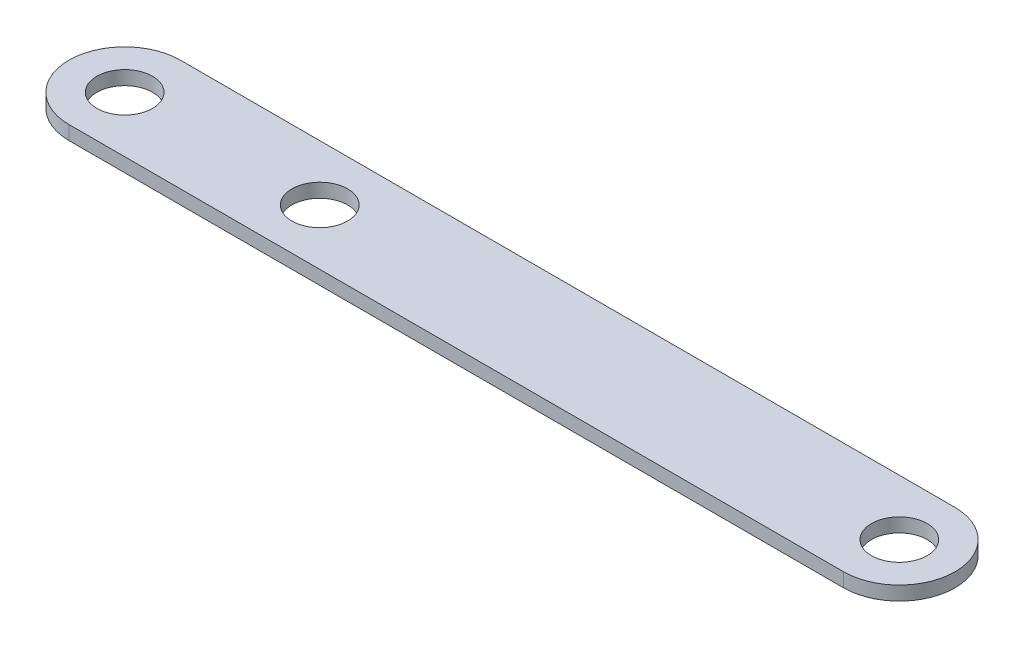
SolidWorks part; units mm, degrees
ref_plane "Front Plane" through (0, 0, 0) normal (0, 0, 1) x (1, 0, 0)
ref_plane "Top Plane" through (0, 0, 0) normal (0, 1, 0) x (1, 0, 0)
ref_plane "Right Plane" through (0, 0, 0) normal (1, 0, 0) x (0, 0, -1)
sketch "Sketch1" plane through (0, 0, 0) normal (0, 1, 0) x (1, 0, 0)
  line L0 (0, 0) -> (176.5478, 0) construction
  line L1 (0, 12.7) -> (176.5478, 12.7)
  line L2 (0, -12.7) -> (176.5478, -12.7)
  arc A0 (0, 12.7) -> (0, -12.7) centre (0, 0) ccw
  arc A1 (176.5478, -12.7) -> (176.5478, 12.7) centre (176.5478, 0) ccw
  circle A2 centre (0, 0) radius 6.35
  circle A3 centre (44.45, 0) radius 6.35
  circle A4 centre (176.5478, 0) radius 6.35
  point P3 (88.2739, 0)
  dimension "D2" = 12.7
  dimension "D3" = 12.7
  dimension "D4" = 12.7
  dimension "D6" = 12.7
  dimension "D1" = 176.5478
  dimension "D5" = 44.45
extrude "Boss-Extrude1" add sketch "Sketch1" along normal blind 3.175
